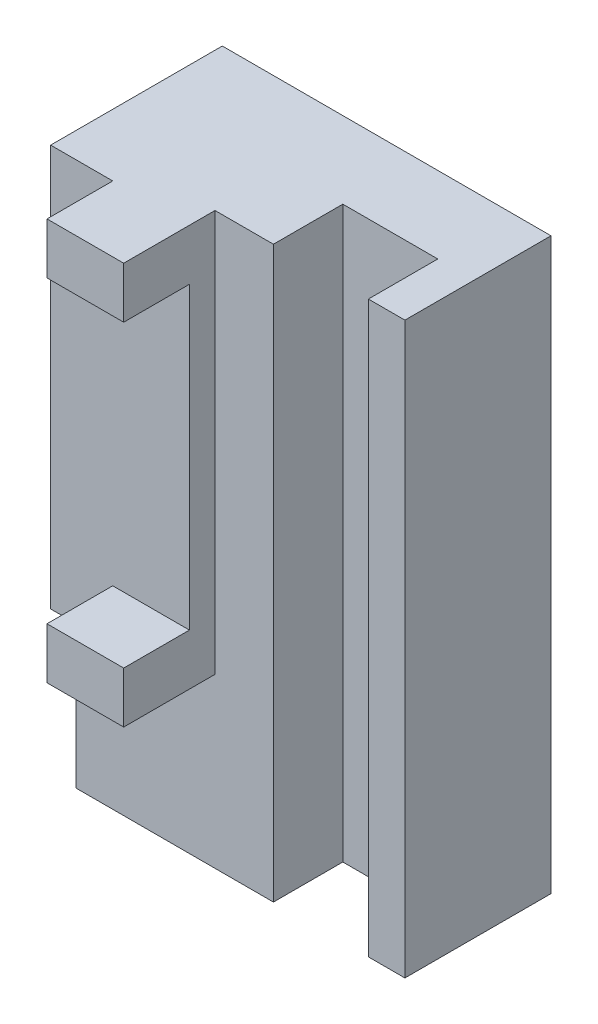
SolidWorks part; units mm, degrees
ref_plane "Front Plane" through (0, 0, 0) normal (0, 0, 1) x (1, 0, 0)
ref_plane "Top Plane" through (0, 0, 0) normal (0, 1, 0) x (1, 0, 0)
ref_plane "Right Plane" through (0, 0, 0) normal (1, 0, 0) x (0, 0, -1)
sketch "Sketch4" plane through (0, 0, 0) normal (0, 0, 1) x (1, 0, 0)
  line L1 (-28.7781, 55.5758) -> (16.2219, 55.5758)
  line L2 (-28.7781, 55.5758) -> (-28.7781, -22.4242)
  line L3 (-28.7781, -22.4242) -> (16.2219, -22.4242)
  line L4 (16.2219, 55.5758) -> (16.2219, -22.4242)
  dimension "D1" = 78
  dimension "D2" = 45
extrude "Boss-Extrude1" add sketch "Sketch4" along normal blind 20
sketch "Sketch6" plane through (0, -22.4242, 0) normal (0, -1, 0) x (1, 0, 0)
  line L0 (-28.7781, 20) -> (16.2219, 20) construction
  line L1 (-1.7781, 20) -> (11.2219, 20)
  line L2 (-1.7781, 20) -> (-1.7781, 10.5)
  line L3 (-1.7781, 10.5) -> (11.2219, 10.5)
  line L4 (11.2219, 20) -> (11.2219, 10.5)
  line L5 (16.2219, 20) -> (16.2219, 0) construction
  dimension "D1" = 9.5
  dimension "D2" = 13
  dimension "D3" = 5
extrude "Cut-Extrude1" cut sketch "Sketch6" against normal through all
sketch "Sketch7" plane through (0, 0, 20) normal (0, 0, 1) x (1, 0, 0)
  line L0 (-1.7781, 55.5758) -> (-28.7781, 55.5758) construction
  line L1 (-20.2781, 55.5758) -> (-9.7781, 55.5758)
  line L2 (-20.2781, 55.5758) -> (-20.2781, 0.5758)
  line L3 (-20.2781, 0.5758) -> (-9.7781, 0.5758)
  line L4 (-9.7781, 55.5758) -> (-9.7781, 0.5758)
  line L5 (-1.7781, 55.5758) -> (-1.7781, -22.4242) construction
  dimension "D1" = 55
  dimension "D2" = 8
  dimension "D3" = 10.5
extrude "Boss-Extrude2" add sketch "Sketch7" along normal blind 3.5
sketch "Sketch8" plane through (0, 0, 23.5) normal (0, 0, 1) x (1, 0, 0)
  line L0 (-20.2781, 55.5758) -> (-20.2781, 0.5758) construction
  line L1 (-9.7781, 0.5758) -> (-20.2781, 0.5758)
  line L2 (-9.7781, 0.5758) -> (-9.7781, 7.5758)
  line L3 (-9.7781, 7.5758) -> (-20.2781, 7.5758)
  line L4 (-20.2781, 0.5758) -> (-20.2781, 7.5758)
  line L5 (-9.7781, 0.5758) -> (-9.7781, 55.5758) construction
  line L6 (-20.2781, 55.5758) -> (-9.7781, 55.5758)
  line L7 (-20.2781, 55.5758) -> (-20.2781, 48.5758)
  line L8 (-20.2781, 48.5758) -> (-9.7781, 48.5758)
  line L9 (-9.7781, 55.5758) -> (-9.7781, 48.5758)
  dimension "D1" = 7
  dimension "D2" = 7
extrude "Boss-Extrude3" add sketch "Sketch8" along normal blind 9
sketch "Sketch9" plane through (0, 0, 20) normal (0, 0, 1) x (1, 0, 0)
  line L0 (-28.7781, 55.5758) -> (-28.7781, -22.4242) construction
  line L1 (-20.2781, 55.5758) -> (-28.7781, 55.5758)
  line L2 (-20.2781, 55.5758) -> (-20.2781, 0.5758)
  line L3 (-20.2781, 0.5758) -> (-28.7781, 0.5758)
  line L4 (-28.7781, 55.5758) -> (-28.7781, 0.5758)
extrude "Boss-Extrude4" add sketch "Sketch9" along normal blind 3.5
